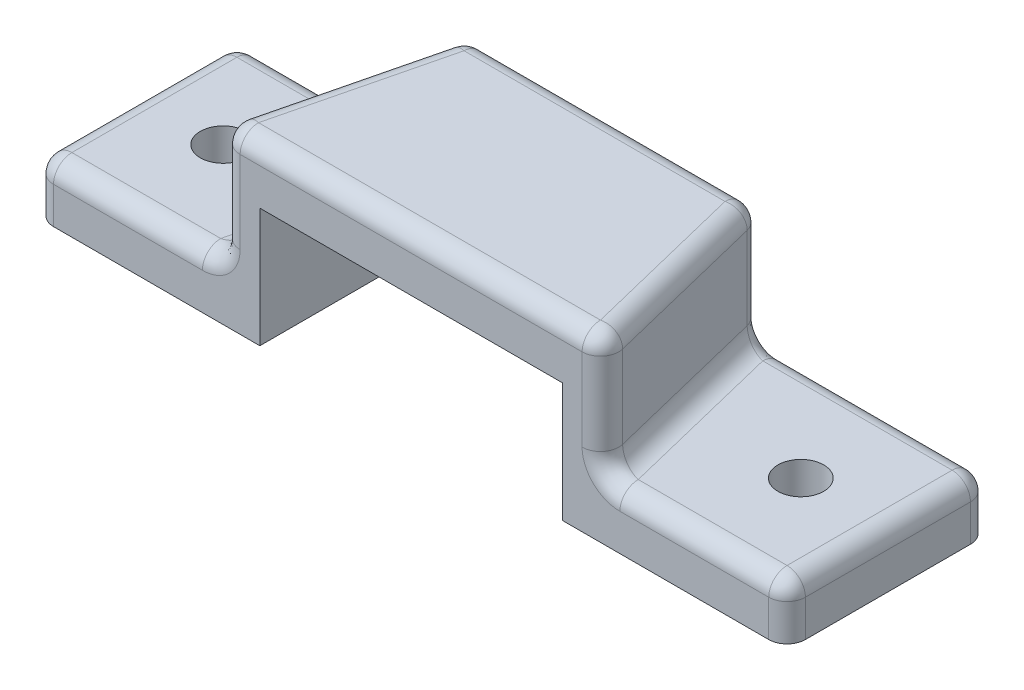
SolidWorks part; units mm, degrees
ref_plane "Front Plane" through (0, 0, 0) normal (0, 0, 1) x (1, 0, 0)
ref_plane "Top Plane" through (0, 0, 0) normal (0, 1, 0) x (1, 0, 0)
ref_plane "Right Plane" through (0, 0, 0) normal (1, 0, 0) x (0, 0, -1)
sketch "Sketch1" plane through (0, 0, 0) normal (0, 1, 0) x (1, 0, 0)
  line L0 (0, -13.97) -> (0, 13.97) construction
  line L1 (-52.07, -13.97) -> (52.07, -13.97)
  line L2 (-52.07, -13.97) -> (-52.07, 13.97)
  line L3 (-52.07, 13.97) -> (52.07, 13.97)
  line L4 (52.07, -13.97) -> (52.07, 13.97)
  line L5 (-52.07, -13.97) -> (52.07, 13.97) construction
  line L6 (-52.07, 13.97) -> (52.07, -13.97) construction
  circle A0 centre (40.005, 0) radius 3.175
  circle A1 centre (-40.005, 0) radius 3.175
  point P0 (0, 0)
  point P10 (0, 0)
  point P11 (-52.07, 0)
  point P14 (0, 13.97)
  point P15 (0, 0)
  point P16 (40.005, 0)
  dimension "D3" = 80.01
  dimension "D4" = 6.35
  dimension "D1" = 27.94
  dimension "D2" = 104.14
extrude "Boss-Extrude1" add sketch "Sketch1" along normal blind 24.13
sketch "Sketch2" plane through (0, 0, 0) normal (0, -1, 0) x (1, 0, 0)
  line L0 (-52.07, 13.97) -> (52.07, 13.97) construction
  line L1 (-20.955, -6.35) -> (20.955, -6.35)
  line L2 (-20.955, -6.35) -> (-20.955, 13.97)
  line L3 (-20.955, 13.97) -> (20.955, 13.97)
  line L4 (20.955, -6.35) -> (20.955, 13.97)
  point P6 (0, -6.35)
  dimension "D1" = 20.32
  dimension "D2" = 41.91
extrude "Cut-Extrude1" cut sketch "Sketch2" against normal blind 16.51
sketch "Sketch4" plane through (0, 24.13, 0) normal (0, 1, 0) x (1, 0, 0)
  line L1 (-52.07, -13.97) -> (-26.924, -13.97)
  line L2 (-52.07, -13.97) -> (-52.07, 13.97)
  line L3 (-52.07, 13.97) -> (-20.066, 13.97)
  line L5 (52.07, 13.97) -> (-52.07, 13.97) construction
  line L6 (0, 0) -> (0, 50000) construction
  line L7 (52.07, 13.97) -> (20.066, 13.97)
  line L9 (52.07, -13.97) -> (26.924, -13.97)
  line L10 (52.07, -13.97) -> (52.07, 13.97)
  line L11 (-20.066, 13.97) -> (-26.924, -13.97)
  line L12 (20.066, 13.97) -> (26.924, -13.97)
  line L13 (-23.495, 0) -> (23.495, 0) construction
  point P20 (-40.005, 0)
  dimension "D1" = 27.94
  dimension "D2" = 40.132
  dimension "D3" = 46.99
extrude "Cut-Extrude2" cut sketch "Sketch4" against normal blind 16.51
fillet "Fillet1" radius 2.54 23 edges at (36.068, 7.62, -13.97) (39.497, 7.62, 13.97) (-39.497, 7.62, 13.97) (-36.068, 7.62, -13.97) (20.066, 15.875, -13.97) (23.495, 7.62, 0) (26.924, 15.875, 13.97) (-26.924, 15.875, 13.97) (-23.495, 7.62, 0) (-20.066, 15.875, -13.97) (23.495, 24.13, 0) (0, 24.13, 13.97) (-23.495, 24.13, 0) (0, 24.13, -13.97) (0, 16.51, -6.35) (20.955, 8.255, -6.35) (-20.955, 8.255, -6.35) (-52.07, 3.81, -13.97) (-52.07, 7.62, 0) (-52.07, 3.81, 13.97) (52.07, 3.81, -13.97) (52.07, 3.81, 13.97) (52.07, 7.62, 0)
